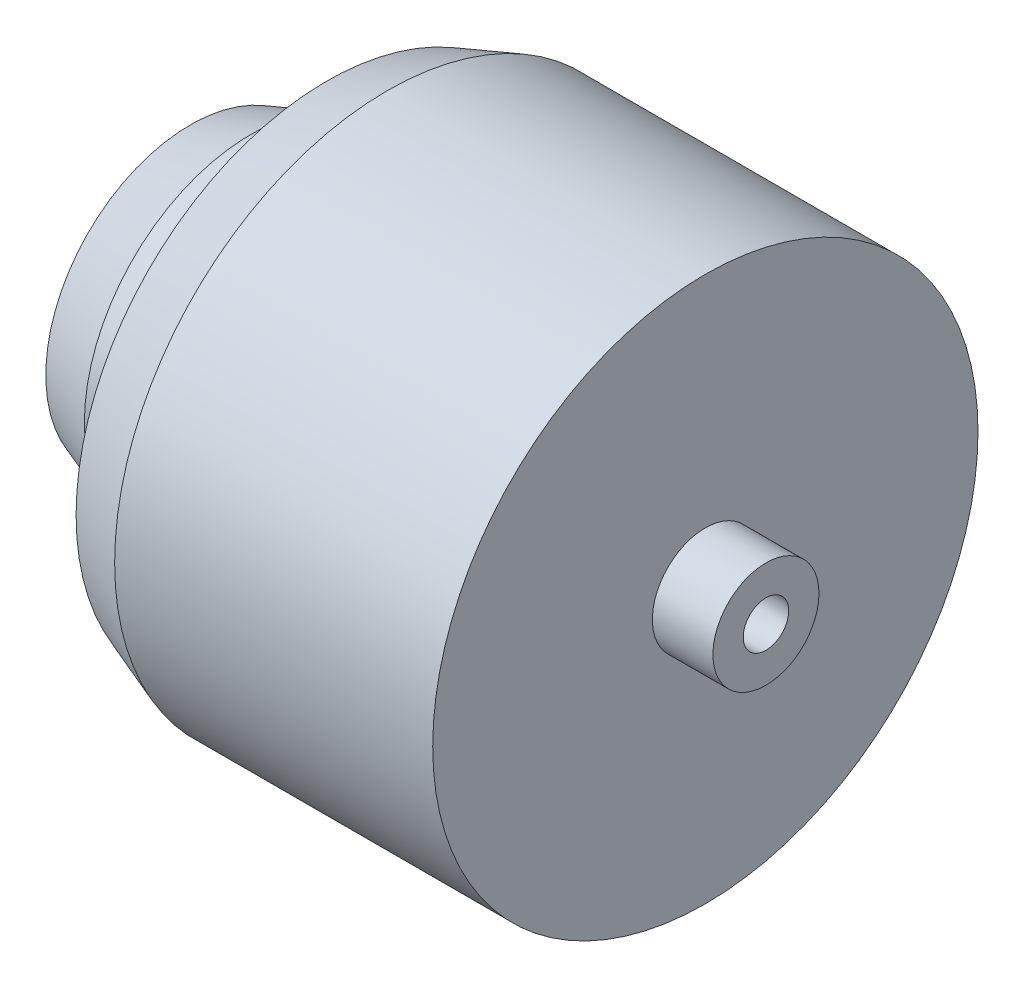
SolidWorks part; units mm, degrees
material "PVC 0.007 Plasticized"
ref_plane "Front Plane" through (0, 0, 0) normal (0, 0, 1) x (1, 0, 0)
ref_plane "Top Plane" through (0, 0, 0) normal (0, 1, 0) x (1, 0, 0)
ref_plane "Right Plane" through (0, 0, 0) normal (1, 0, 0) x (0, 0, -1)
sketch "Sketch1" plane through (0, 0, 0) normal (1, 0, 0) x (0, 0, -1)
  circle A0 centre (0, 0) radius 18
  dimension "D1" = 36
extrude "Boss-Extrude1" add sketch "Sketch1" along normal blind 38
sketch "Sketch2" plane through (38, 0, 0) normal (1, 0, 0) x (0, 0, -1)
  circle A0 centre (0, 0) radius 3.5
  dimension "D1" = 7
extrude "Cut-Extrude1" cut sketch "Sketch2" against normal blind 4 flip side to cut
sketch "Sketch3" plane through (0, 0, 0) normal (-1, 0, 0) x (0, 0, 1)
  circle A0 centre (0, 0) radius 11
  dimension "D1" = 22
extrude "Cut-Extrude2" cut sketch "Sketch3" against normal blind 9 flip side to cut
chamfer "Chamfer1" distance 4 angle 20 2 edges at (0, 0, 11) (9, 0, 18)
hole_wizard "Ø3.0 (3) Diameter Hole1" positions "Sketch6" profile "Sketch7" hole size "Ø3.0" standard "ISO"
sketch "Sketch6" plane through (38, 0, 0) normal (1, 0, 0) x (0, 0, -1)
  point P0 (0, 0)
sketch "Sketch7" plane through (38, 0, 0) normal (0, 1, 0) x (0, 0, -1)
  line L0 (0, 0) -> (0, 35)
  line L1 (0, 35) -> (1.5, 34.0987)
  line L2 (1.5, 34.0987) -> (1.5, 0)
  line L5 (1.5, 0) -> (0, 0)
  line L10 (0, 35) -> (-1.5, 34.0987) construction
  line L11 (0, -6.35) -> (0, 107.95) construction
  dimension "Hole Dia." = 3
  dimension "Hole Depth" = 35
  dimension "Drill Angle" = 118
